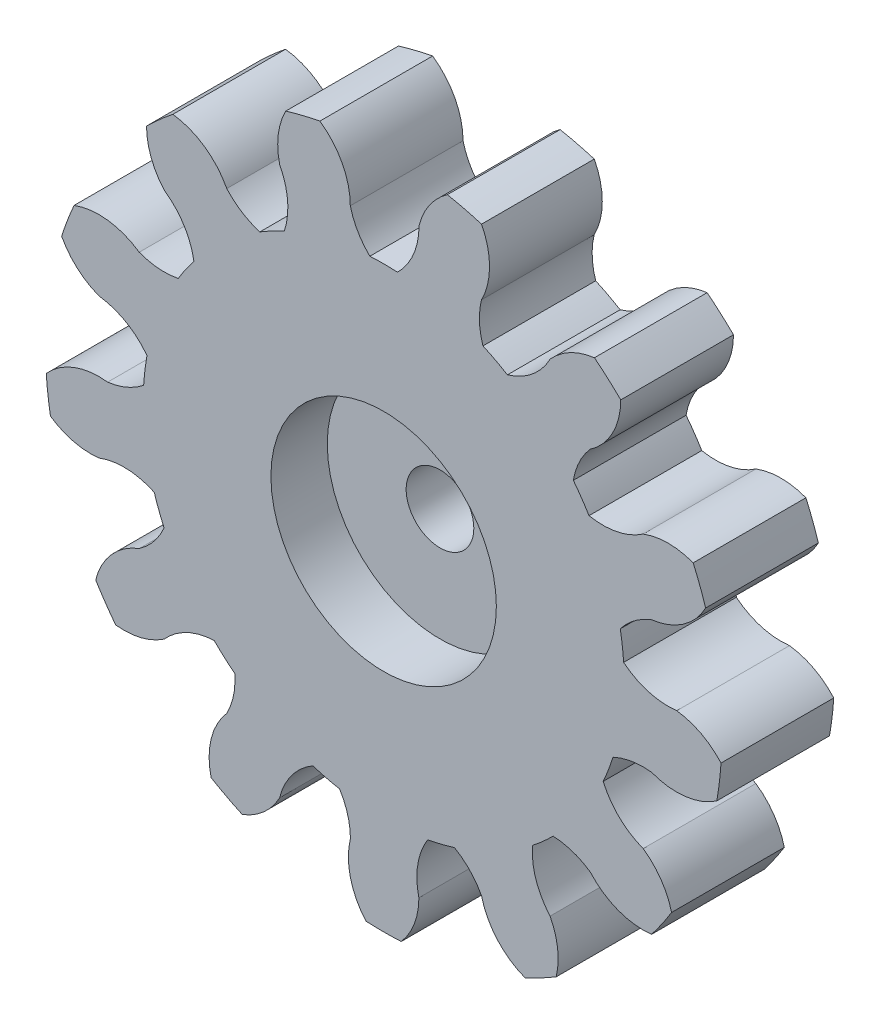
SolidWorks part; units mm, degrees
ref_plane "Alzado" through (0, 0, 0) normal (0, 0, 1) x (1, 0, 0)
ref_plane "Planta" through (0, 0, 0) normal (0, 1, 0) x (1, 0, 0)
ref_plane "Vista lateral" through (0, 0, 0) normal (1, 0, 0) x (0, 0, -1)
sketch "Croquis1" plane through (0, 0, 0) normal (0, 0, 1) x (1, 0, 0)
  circle A0 centre (0, 0) radius 15
  circle A1 centre (0, 0) radius 1.5
  dimension "D1" = 30
  dimension "D2" = 3
extrude "Saliente-Extruir1" add sketch "Croquis1" along normal blind 5
sketch "Croquis2" plane through (0, 0, 5) normal (0, 0, 1) x (1, 0, 0)
  arc A0 (2.8274, 14.7311) -> (-2.8274, 14.7311) centre (0, 0) ccw
  arc A1 (0.6125, 10.6474) -> (-0.6125, 10.6474) centre (0, 0) ccw
  arc A3 (-1.4784, 12.152) -> (-2.8274, 14.7311) centre (-4.6184, 12.152) ccw
  arc A5 (-1.4784, 12.152) -> (-0.6125, 10.6474) centre (1.57, 12.9048) ccw
  arc A8 (2.8274, 14.7311) -> (1.57, 12.9048) centre (4.6184, 12.152) ccw
  arc A10 (0.6125, 10.6474) -> (1.57, 12.9048) centre (-1.57, 12.9048) ccw
  dimension "D1" = 21.33
  dimension "D3" = 6.28
extrude "Cortar-Extruir1" cut sketch "Croquis2" against normal through all
pattern_circular "MatrizC1" count 13 over 360 about axis through (0, 0, 0) along (0, 0, 1) of "Cortar-Extruir1"
sketch "Croquis3" plane through (0, 0, 5) normal (0, 0, 1) x (1, 0, 0)
  circle A0 centre (0, 0) radius 5
  dimension "D1" = 10
extrude "Cortar-Extruir2" cut sketch "Croquis3" against normal blind 2.5
